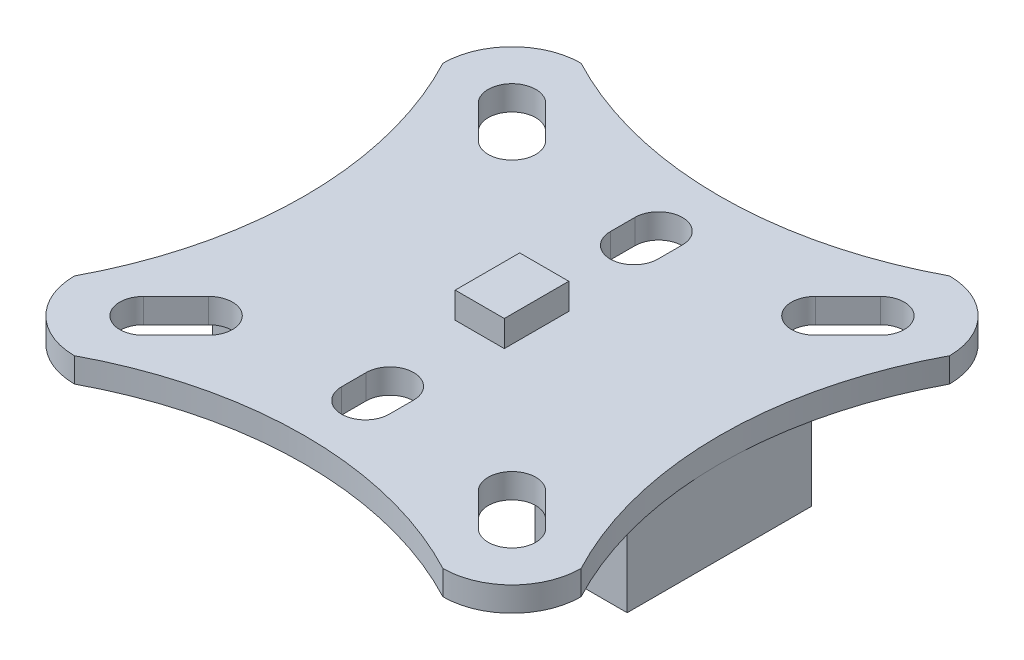
SolidWorks part; units mm, degrees
ref_plane "Front Plane" through (0, 0, 0) normal (0, 0, 1) x (1, 0, 0)
ref_plane "Top Plane" through (0, 0, 0) normal (0, 1, 0) x (1, 0, 0)
ref_plane "Right Plane" through (0, 0, 0) normal (1, 0, 0) x (0, 0, -1)
sketch "Sketch1" plane through (0, 0, 0) normal (0, 1, 0) x (1, 0, 0)
  line L0 (0, 26.05) -> (33, 26.05) construction
  line L1 (0, 0) -> (33, 0)
  line L2 (0, 0) -> (0, 33)
  line L3 (0, 33) -> (33, 33)
  line L4 (33, 0) -> (33, 33)
  line L13 (0, 24.45) -> (33, 24.45) construction
  line L14 (0, 16.5) -> (33, 16.5) construction
  line L15 (16.5, 33) -> (16.5, 0) construction
  line L16 (0, 0) -> (33, 33) construction
  line L17 (0, 13.2426) -> (13.2426, 0) construction
  line L18 (0, 9) -> (9, 0) construction
  line L19 (4.5, 4.5) -> (6.6213, 6.6213) construction
  line L22 (16.5, 26.05) -> (16.5, 24.45) construction
  line L23 (18.05, 26.05) -> (18.05, 24.45)
  line L24 (14.95, 26.05) -> (14.95, 24.45)
  line L25 (3.404, 5.596) -> (5.5253, 7.7173)
  line L26 (5.596, 3.404) -> (7.7173, 5.5253)
  line L27 (28.5, 4.5) -> (26.3787, 6.6213) construction
  line L28 (29.596, 5.596) -> (27.4747, 7.7173)
  line L29 (27.404, 3.404) -> (25.2827, 5.5253)
  line L30 (33, 9) -> (24, 0) construction
  line L31 (33, 13.2426) -> (19.7574, 0) construction
  line L32 (33, 0) -> (0, 33) construction
  line L33 (33, 19.7574) -> (19.7574, 33) construction
  line L34 (33, 24) -> (24, 33) construction
  line L35 (0, 24) -> (9, 33) construction
  line L36 (0, 19.7574) -> (13.2426, 33) construction
  line L37 (16.5, 6.95) -> (16.5, 8.55) construction
  line L38 (18.05, 6.95) -> (18.05, 8.55)
  line L39 (14.95, 6.95) -> (14.95, 8.55)
  line L40 (0, 8.55) -> (33, 8.55) construction
  line L41 (0, 6.95) -> (33, 6.95) construction
  line L42 (4.5, 28.5) -> (6.6213, 26.3787) construction
  line L43 (5.596, 29.596) -> (7.7173, 27.4747)
  line L44 (3.404, 27.404) -> (5.5253, 25.2827)
  line L45 (26.3787, 26.3787) -> (28.5, 28.5) construction
  line L46 (25.2827, 27.4747) -> (27.404, 29.596)
  line L47 (27.4747, 25.2827) -> (29.596, 27.404)
  arc A2 (18.05, 26.05) -> (14.95, 26.05) centre (16.5, 26.05) ccw
  arc A3 (14.95, 24.45) -> (18.05, 24.45) centre (16.5, 24.45) ccw
  arc A4 (3.404, 5.596) -> (5.596, 3.404) centre (4.5, 4.5) ccw
  arc A5 (7.7173, 5.5253) -> (5.5253, 7.7173) centre (6.6213, 6.6213) ccw
  arc A7 (0, 4.5) -> (4.5, 0) centre (4.5, 4.5) ccw
  arc A8 (29.596, 5.596) -> (27.404, 3.404) centre (28.5, 4.5) cw
  arc A9 (25.2827, 5.5253) -> (27.4747, 7.7173) centre (26.3787, 6.6213) cw
  arc A10 (33, 4.5) -> (28.5, 0) centre (28.5, 4.5) cw
  arc A11 (33, 28.5) -> (28.5, 33) centre (28.5, 28.5) ccw
  arc A12 (0, 28.5) -> (4.5, 33) centre (4.5, 28.5) cw
  arc A13 (18.05, 6.95) -> (14.95, 6.95) centre (16.5, 6.95) cw
  arc A14 (14.95, 8.55) -> (18.05, 8.55) centre (16.5, 8.55) cw
  arc A15 (5.596, 29.596) -> (3.404, 27.404) centre (4.5, 28.5) ccw
  arc A16 (5.5253, 25.2827) -> (7.7173, 27.4747) centre (6.6213, 26.3787) ccw
  arc A17 (25.2827, 27.4747) -> (27.4747, 25.2827) centre (26.3787, 26.3787) ccw
  arc A18 (29.596, 27.404) -> (27.404, 29.596) centre (28.5, 28.5) ccw
  arc A19 (0, 28.5) -> (0, 4.5) centre (-22.6133, 16.5) cw
  arc A20 (33, 28.5) -> (33, 4.5) centre (55.6133, 16.5) ccw
  arc A21 (4.5, 33) -> (28.5, 33) centre (16.5, 55.6133) ccw
  arc A22 (4.5, 0) -> (28.5, 0) centre (16.5, -22.6133) cw
  point P19 (5.5607, 5.5607)
  point P21 (4.5, 4.5)
  point P25 (16.5, 25.25)
  point P37 (27.4393, 5.5607)
  point P65 (16.5, 7.75)
  point P74 (5.5607, 27.4393)
  point P80 (27.4393, 27.4393)
  point P86 (16.5, 30.0133)
  point P89 (2.9867, 16.5)
  dimension "D6" = 3.1
  dimension "D8" = 4.5
  dimension "D9" = 3.1
  dimension "D11" = 25.6
  dimension "D12" = 25.6
  dimension "D1" = 33
  dimension "D2" = 7.95
  dimension "D3" = 9.55
  dimension "D4" = 12
  dimension "D5" = 3
  dimension "D7" = 3.1
  dimension "D10" = 3.1
extrude "Boss-Extrude1" add sketch "Sketch1" along normal blind 1.6 contours A12 L2 A7 L1 A10 L4 A11 L3 A18 L47 A17 L46 A16 L44 A15 L43 A5 L26 A4 L25 A3 L24 A2 L23 L29 A9 L28 A8 L39 A14 L38 A13
sketch "Sketch2" plane through (0, 1.6, 0) normal (0, 1, 0) x (1, 0, 0)
  line L1 (14.9, 18.6) -> (18.1, 18.6)
  line L2 (14.9, 18.6) -> (14.9, 14.4)
  line L3 (14.9, 14.4) -> (18.1, 14.4)
  line L4 (18.1, 18.6) -> (18.1, 14.4)
  line L5 (0, 0) -> (33, 0) construction
  line L6 (0, 0) -> (0, 33) construction
  line L7 (0, 33) -> (33, 33) construction
  line L8 (33, 0) -> (33, 33) construction
  arc A0 (33, 28.5) -> (28.5, 33) centre (28.5, 28.5) ccw construction
  point P12 (16.5, 33)
  point P13 (16.5, 18.6)
  point P14 (0, 16.5)
  point P15 (14.9, 16.5)
  dimension "D1" = 4.2
  dimension "D2" = 3.2
extrude "Boss-Extrude2" add sketch "Sketch2" along normal blind 1.7 contours L4 L3 L2 L1
sketch "Sketch3" plane through (0, 0, 0) normal (0, -1, 0) x (1, 0, 0)
  line L0 (16.5, 0) -> (16.5, -33) construction
  line L1 (3, -10.5) -> (9, -10.5)
  line L2 (3, -10.5) -> (3, -22.5)
  line L3 (3, -22.5) -> (9, -22.5)
  line L4 (9, -10.5) -> (9, -22.5)
  line L9 (0, 0) -> (33, 0) construction
  line L10 (0, 0) -> (0, -33) construction
  line L11 (0, -33) -> (33, -33) construction
  line L12 (33, 0) -> (33, -33) construction
  line L13 (30, -22.5) -> (24, -22.5)
  line L14 (24, -10.5) -> (24, -22.5)
  line L15 (30, -10.5) -> (24, -10.5)
  line L16 (30, -10.5) -> (30, -22.5)
  arc A0 (28.5, -33) -> (33, -28.5) centre (28.5, -28.5) ccw construction
  point P16 (3, -16.5)
  point P17 (0, -16.5)
  dimension "D1" = 3
  dimension "D2" = 12
  dimension "D3" = 6
extrude "Boss-Extrude3" add sketch "Sketch3" along normal blind 5.4
